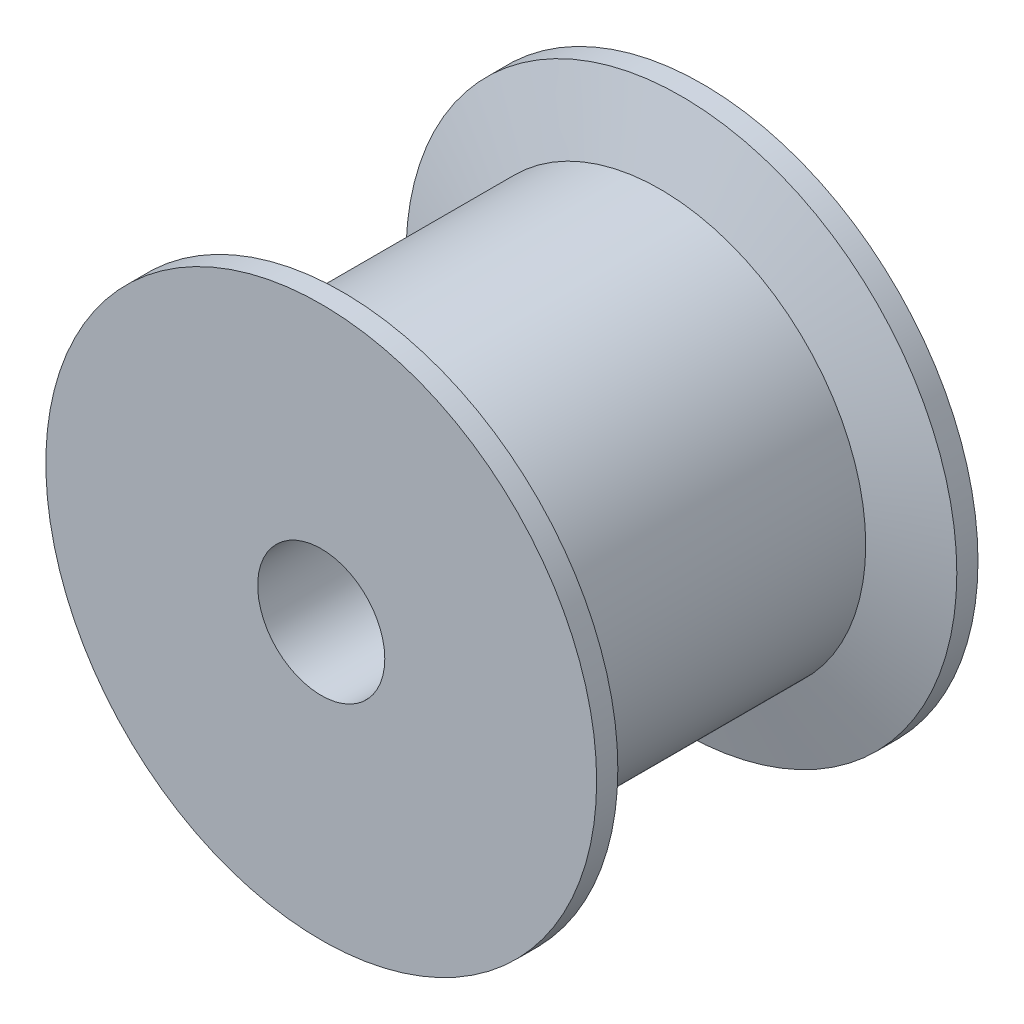
SolidWorks part; units mm, degrees
material "Силиконовая резина"
ref_plane "Спереди" through (0, 0, 0) normal (0, 0, 1) x (1, 0, 0)
ref_plane "Сверху" through (0, 0, 0) normal (0, 1, 0) x (1, 0, 0)
ref_plane "Справа" through (0, 0, 0) normal (1, 0, 0) x (0, 0, -1)
sketch "Эскиз1" plane through (0, 0, 0) normal (1, 0, 0) x (0, 0, -1)
  line L2 (3.5, 4.85) -> (4, 6.5)
  line L3 (4, 6.5) -> (4.5, 6.5)
  line L9 (3.5, 4.85) -> (-3.5, 4.85)
  line L11 (-4, 6.5) -> (-4.5, 6.5)
  line L12 (-4.5, 6.5) -> (-4.5, 1.5)
  line L13 (-4.5, 1.5) -> (4.5, 1.5)
  line L14 (4.5, 1.5) -> (4.5, 6.5)
  line L15 (0, 0) -> (3.5, 0) construction
  line L16 (-4, 6.5) -> (-3.5, 4.85)
  point P0 (0, 4.85)
  point P10 (0, 1.5)
  dimension "D1" = 9
  dimension "D2" = 0.5
  dimension "D3" = 1.5
  dimension "D4" = 4.85
  dimension "D5" = 6.5
  dimension "D6" = 7
revolve "Повернуть1" add sketch "Эскиз1" angle 360 about L15
